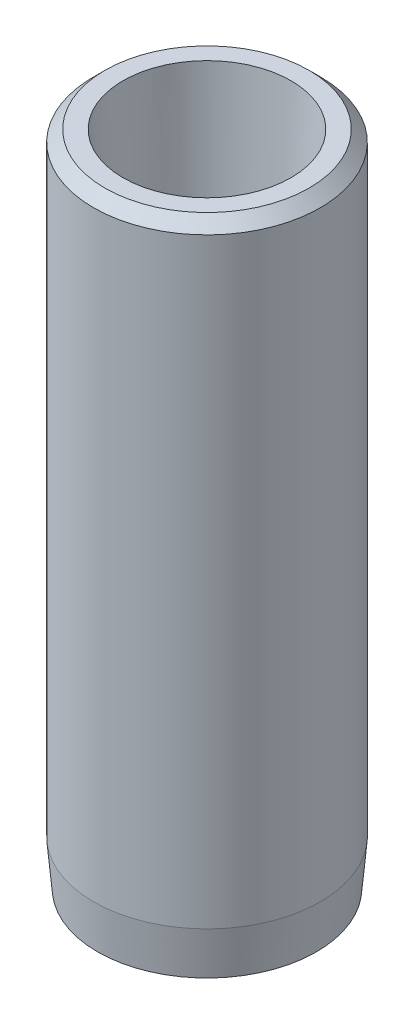
SolidWorks part; units mm, degrees
material "K110"
ref_plane "Front Plane" through (0, 0, 0) normal (0, 0, 1) x (1, 0, 0)
ref_plane "Top Plane" through (0, 0, 0) normal (0, 1, 0) x (1, 0, 0)
ref_plane "Right Plane" through (0, 0, 0) normal (1, 0, 0) x (0, 0, -1)
sketch "Sketch1" plane through (0, 0, 0) normal (0, 1, 0) x (1, 0, 0)
  circle A0 centre (0, 0) radius 2.5
  circle A1 centre (0, 0) radius 5
  dimension "ID" = 5
  dimension "OD" = 10
extrude "Boss-Extrude1" add sketch "Sketch1" along normal blind 29
sketch "Sketch2" plane through (0, 0, 0) normal (0, 0, 1) x (1, 0, 0)
  line L0 (2.5, 6) -> (3.7054, 29)
  line L1 (2.5, 0) -> (2.5, 29) construction
  line L2 (5, 29) -> (-5, 29) construction
  line L3 (3.7054, 29) -> (2.5, 29)
  line L4 (2.5, 29) -> (2.5, 6)
  line L5 (5.5, 0) -> (-5.5, 0) construction
  dimension "D1" = 6
  dimension "D2" = 3
sweep "Cut-Sweep1" cut profiles "Sketch2" path edge at (0, 29, 2.5)
chamfer "Chamfer1" distance 2 angle 5 1 edges at (0, 0, 5)
chamfer "Chamfer2" distance 0.5 angle 45 1 edges at (0, 29, 5)
